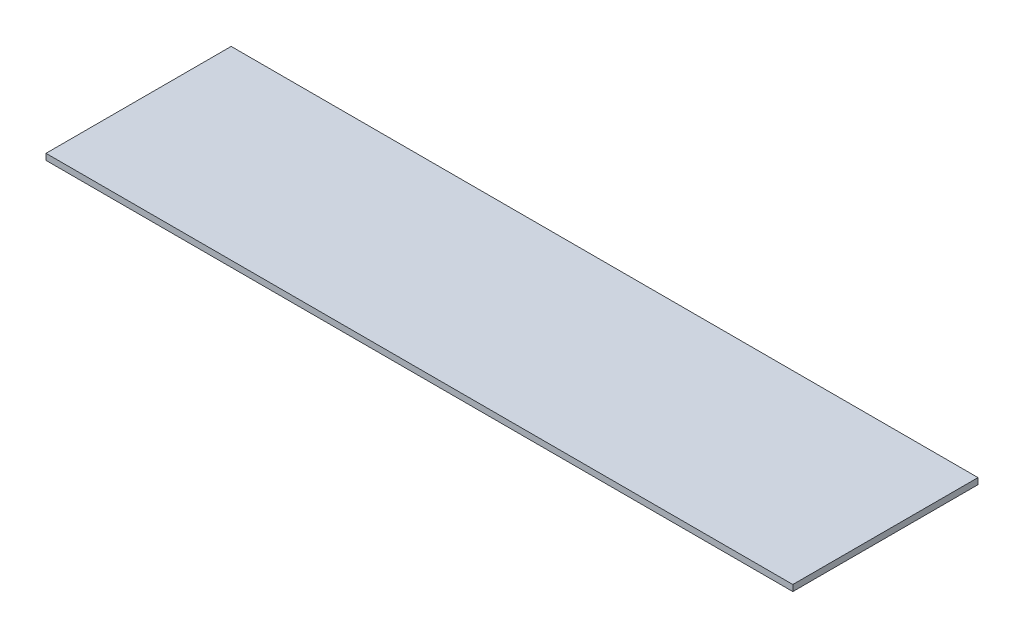
SolidWorks part; units mm, degrees
ref_plane "Front Plane" through (0, 0, 0) normal (0, 0, 1) x (1, 0, 0)
ref_plane "Top Plane" through (0, 0, 0) normal (0, 1, 0) x (1, 0, 0)
ref_plane "Right Plane" through (0, 0, 0) normal (1, 0, 0) x (0, 0, -1)
sketch "Esquisse1" plane through (0, 0, 0) normal (0, 1, 0) x (1, 0, 0)
  line L1 (-605, -150) -> (605, -150)
  line L2 (-605, -150) -> (-605, 150)
  line L3 (-605, 150) -> (605, 150)
  line L4 (605, -150) -> (605, 150)
  line L5 (-605, -150) -> (605, 150) construction
  line L6 (-605, 150) -> (605, -150) construction
  point P0 (0, 0)
extrude "Boss.-Extru.1" add sketch "Esquisse1" along normal blind 10
